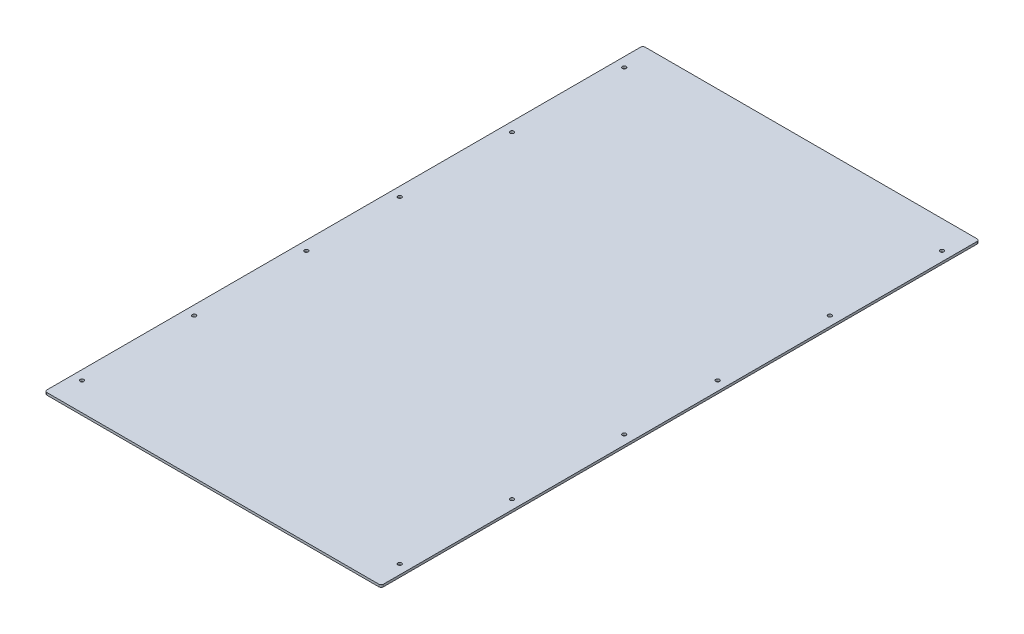
SolidWorks part; units mm, degrees
material "PC High Viscosity"
ref_plane "Front Plane" through (0, 0, 0) normal (0, 0, 1) x (1, 0, 0)
ref_plane "Top Plane" through (0, 0, 0) normal (0, 1, 0) x (1, 0, 0)
ref_plane "Right Plane" through (0, 0, 0) normal (1, 0, 0) x (0, 0, -1)
sketch "Sketch1" plane through (0, 0, 0) normal (0, 1, 0) x (1, 0, 0)
  line L1 (-228.6, -406.4) -> (228.6, -406.4)
  line L2 (-228.6, -406.4) -> (-228.6, 406.4)
  line L3 (-228.6, 406.4) -> (228.6, 406.4)
  line L4 (228.6, -406.4) -> (228.6, 406.4)
  line L5 (-228.6, -406.4) -> (228.6, 406.4) construction
  line L6 (-228.6, 406.4) -> (228.6, -406.4) construction
  point P0 (0, 0)
  dimension "D1" = 457.2
  dimension "D2" = 812.8
extrude "Boss-Extrude1" add sketch "Sketch1" along normal blind 3.175
hole_wizard "#7 (0.201) Diameter Hole1" positions "Sketch2" profile "Sketch3" hole size "#7" standard "ANSI Inch"
sketch "Sketch2" plane through (0, 3.175, 0) normal (0, 1, 0) x (1, 0, 0)
  line L0 (228.6, 406.4) -> (-228.6, 406.4) construction
  line L1 (-228.6, 406.4) -> (-228.6, -406.4) construction
  point P0 (-215.9, 368.3)
  point P13 (215.9, 368.3)
  point P19 (215.9, 215.9)
  point P25 (215.9, 63.5)
  point P30 (215.9, -63.5)
  point P36 (215.9, -215.9)
  point P42 (215.9, -368.3)
  point P50 (-215.9, 215.9)
  point P56 (-215.9, 63.5)
  point P61 (-215.9, -63.5)
  point P67 (-215.9, -215.9)
  point P73 (-215.9, -368.3)
  point P76 (-215.9, 241.3) [skipped]
  point P77 (-215.9, 266.7) [skipped]
  point P78 (-215.9, 292.1) [skipped]
  point P79 (-215.9, 317.5) [skipped]
  point P80 (-215.9, 342.9) [skipped]
  point P81 (215.9, 241.3) [skipped]
  point P82 (215.9, 266.7) [skipped]
  point P83 (215.9, 292.1) [skipped]
  point P84 (215.9, 317.5) [skipped]
  point P85 (215.9, 342.9) [skipped]
  point P88 (-215.9, 88.9) [skipped]
  point P89 (-215.9, 114.3) [skipped]
  point P90 (-215.9, 139.7) [skipped]
  point P91 (-215.9, 165.1) [skipped]
  point P92 (-215.9, 190.5) [skipped]
  point P93 (215.9, 88.9) [skipped]
  point P94 (215.9, 114.3) [skipped]
  point P95 (215.9, 139.7) [skipped]
  point P96 (215.9, 165.1) [skipped]
  point P97 (215.9, 190.5) [skipped]
  point P98 (-215.9, -342.9) [skipped]
  point P99 (-215.9, -317.5) [skipped]
  point P100 (-215.9, -292.1) [skipped]
  point P101 (-215.9, -266.7) [skipped]
  point P102 (-215.9, -241.3) [skipped]
  point P103 (215.9, -342.9) [skipped]
  point P104 (215.9, -317.5) [skipped]
  point P105 (215.9, -292.1) [skipped]
  point P106 (215.9, -266.7) [skipped]
  point P107 (215.9, -241.3) [skipped]
  point P108 (-215.9, -190.5) [skipped]
  point P109 (-215.9, -165.1) [skipped]
  point P110 (-215.9, -139.7) [skipped]
  point P111 (-215.9, -114.3) [skipped]
  point P112 (-215.9, -88.9) [skipped]
  point P113 (215.9, -190.5) [skipped]
  point P114 (215.9, -165.1) [skipped]
  point P115 (215.9, -139.7) [skipped]
  point P116 (215.9, -114.3) [skipped]
  point P117 (215.9, -88.9) [skipped]
  point P118 (-215.9, -38.1) [skipped]
  point P119 (-215.9, -12.7) [skipped]
  point P120 (-215.9, 12.7) [skipped]
  point P121 (-215.9, 38.1) [skipped]
  point P122 (215.9, -38.1) [skipped]
  point P123 (215.9, -12.7) [skipped]
  point P124 (215.9, 12.7) [skipped]
  point P125 (215.9, 38.1) [skipped]
  dimension "D1" = 38.1
  dimension "D2" = 12.7
  dimension "D5" = 152.4
  dimension "D6" = 431.8
  dimension "D3" = 2
  dimension "D4" = 30
sketch "Sketch3" plane through (-215.9, 3.175, -368.3) normal (1, 0, 0) x (0, 0, 1)
  line L0 (0, 0) -> (0, 3.175)
  line L1 (0, 3.175) -> (2.5527, 3.175)
  line L2 (2.5527, 3.175) -> (2.5527, 0)
  line L5 (2.5527, 0) -> (0, 0)
  line L11 (0, -6.35) -> (0, 107.95) construction
  dimension "Thru Hole Dia." = 5.1054
  dimension "Thru Hole Depth" = 3.175
fillet "Fillet1" radius 3.175 4 edges at (228.6, 1.5875, 406.4) (-228.6, 1.5875, 406.4) (228.6, 1.5875, -406.4) (-228.6, 1.5875, -406.4)
